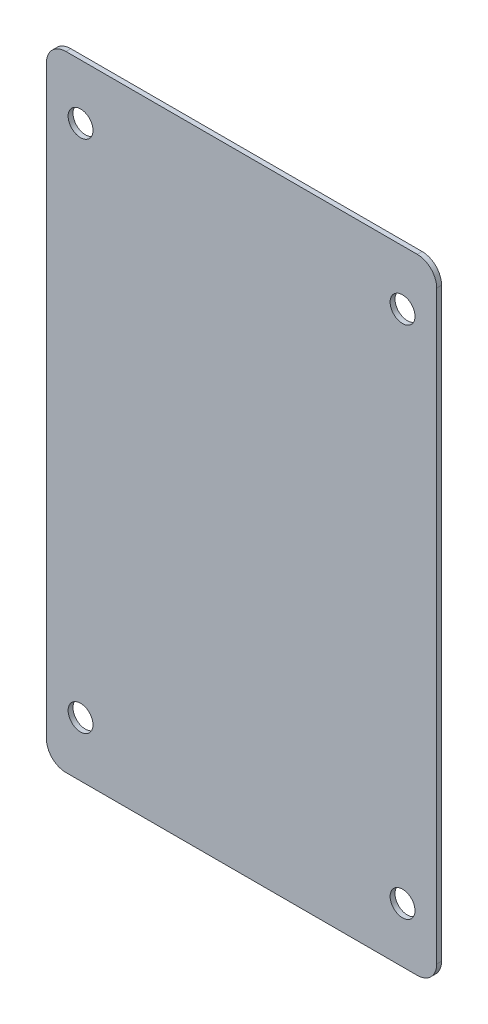
SolidWorks part; units mm, degrees
material "AISI 304"
ref_plane "Front Plane" through (0, 0, 0) normal (0, 0, 1) x (1, 0, 0)
ref_plane "Top Plane" through (0, 0, 0) normal (0, 1, 0) x (1, 0, 0)
ref_plane "Right Plane" through (0, 0, 0) normal (1, 0, 0) x (0, 0, -1)
sketch "Sketch1" plane through (0, 0, 0) normal (0, 0, 1) x (1, 0, 0)
  line L1 (-40, -64) -> (40, -64)
  line L2 (-40, -64) -> (-40, 64)
  line L3 (-40, 64) -> (40, 64)
  line L4 (40, -64) -> (40, 64)
  line L5 (-40, -64) -> (40, 64) construction
  line L6 (-40, 64) -> (40, -64) construction
  point P0 (0, 0)
  dimension "D1" = 80
  dimension "D2" = 128
extrude "Boss-Extrude1" add sketch "Sketch1" along normal blind 1
fillet "Fillet1" radius 4 4 edges at (-40, 64, 0.5) (-40, -64, 0.5) (40, -64, 0.5) (40, 64, 0.5)
sketch "Sketch2" plane through (0, 0, 0) normal (0, 0, -1) x (-1, 0, 0)
  circle A0 centre (-33, -52.75) radius 2.55
  circle A3 centre (-33, 52.75) radius 2.55
  circle A4 centre (33, 52.75) radius 2.55
  circle A5 centre (33, -52.75) radius 2.55
  dimension "D1" = 5.1
extrude "Cut-Extrude1" cut sketch "Sketch2" against normal through all
equation "\"Base-Width\"= 420"
equation "\"Base-Height\"= 320"
equation "\"Support-Rod-Diameter\"= 16"
equation "\"Support-Rod-X-Offset\"= 35"
equation "\"Support-Rod-Y-Offset\"= 35"
equation "\"Base-Thickness\"= 5"
equation "\"Base-Depth\"= 82"
equation "\"Corner-Radius-Major\"= \"Support-Rod-Diameter\""
equation "\"Cutout-Horizontal\"= \"Base-Width\" * 0.8"
equation "\"Cutout-Vertical\"= \"Base-Height\" * 0.6"
equation "\"Outer-Support-Bore-Diameter\"= 6.1"
equation "\"Inner-Support-Bore-Diameter\"= 8.2"
equation "\"Cutout-Depth\"= 20"
equation "\"D1@Sketch1\"=\"Base-Depth\" - 2"
equation "\"D2@Sketch1\"=(\"Base-Height\" - (\"Support-Rod-Diameter\" * 4))/2"
equation "\"D2@Sketch1\"=\"Base-Width\""
equation "\"D1@Sketch7\"=\"Cutout-Vertical\""
equation "\"D2@Sketch6\"=\"Cutout-Horizontal\""
equation "\"D2@Sketch8\"= \"Base-Width\" - ( \"Support-Rod-X-Offset\" ) + 5"
equation "\"D1@Sketch8\" = \"Base-Height\" - \"Support-Rod-Y-Offset\" + 10"
equation "\"D1@Major-Fillet\" = \"Corner-Radius-Major\""
equation "\"D1@Sketch1\"=\"Base-Height\""
